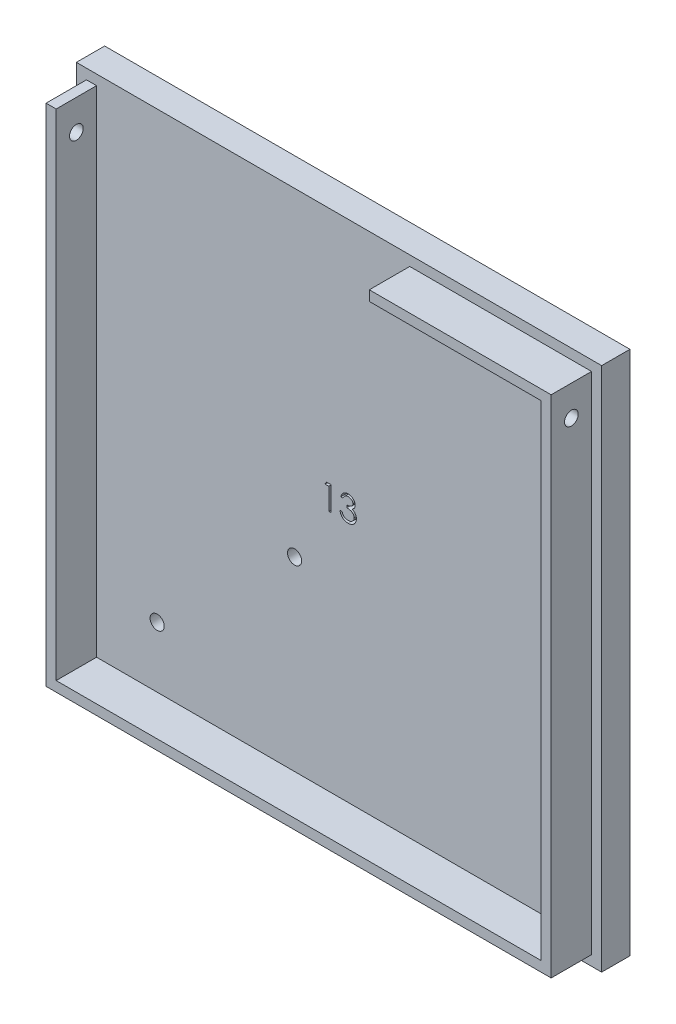
SolidWorks part; units mm, degrees
ref_plane "Alzado" through (0, 0, 0) normal (0, 0, 1) x (1, 0, 0)
ref_plane "Planta" through (0, 0, 0) normal (0, 1, 0) x (1, 0, 0)
ref_plane "Vista lateral" through (0, 0, 0) normal (1, 0, 0) x (0, 0, -1)
sketch "Croquis1" plane through (0, 0, 0) normal (0, 0, 1) x (1, 0, 0)
  line L1 (-65, -65) -> (65, -65)
  line L2 (-65, -65) -> (-65, 65)
  line L3 (-65, 65) -> (65, 65)
  line L4 (65, -65) -> (65, 65)
  circle A0 centre (-11, -14) radius 1.75
  circle A1 centre (-45, -45) radius 1.75
  circle A2 centre (55, 45) radius 2.25
  circle A3 centre (55, -45) radius 2.25
  point P0 (0, 0)
  dimension "D3" = 3.5
  dimension "D6" = 3.5
  dimension "D7" = 34
  dimension "D8" = 20
  dimension "D9" = 4.5
  dimension "D10" = 4.5
  dimension "D11" = 10
  dimension "D12" = 10
  dimension "D13" = 20
  dimension "D4" = 20
  dimension "D5" = 31
  dimension "D14" = 20
  dimension "D1" = 130
  dimension "D2" = 130
extrude "Saliente-Extruir1" add sketch "Croquis1" along normal blind 7
sketch "Croquis2" plane through (0, 0, 7) normal (0, 0, 1) x (1, 0, 0)
  line L0 (-65, 0) -> (65, 0) construction
  line L1 (-65, 65) -> (-65, -65) construction
  line L2 (65, -65) -> (65, 65) construction
  text T0 "13" font "Century Gothic" height 6
extrude "Cortar-Extruir1" cut sketch "Croquis2" against normal blind 2
sketch "Croquis4" plane through (0, 0, 7) normal (0, 0, 1) x (1, 0, 0)
  line L1 (-62.5, -62.5) -> (62.5, -62.5)
  line L2 (-62.5, -62.5) -> (-62.5, 62.5)
  line L3 (-62.5, 62.5) -> (62.5, 62.5)
  line L4 (62.5, -62.5) -> (62.5, 62.5)
  line L5 (-62.5, -62.5) -> (62.5, 62.5) construction
  line L6 (-62.5, 62.5) -> (62.5, -62.5) construction
  line L7 (60, -60) -> (-60, -60)
  line L8 (60, -60) -> (60, 60)
  line L9 (60, 60) -> (-60, 60)
  line L10 (-60, -60) -> (-60, 60)
  line L11 (60, -60) -> (-60, 60) construction
  line L12 (60, 60) -> (-60, -60) construction
  point P0 (0, 0)
  point P6 (0, 0)
  dimension "D1" = 120
  dimension "D2" = 120
  dimension "D3" = 125
extrude "Saliente-Extruir2" add sketch "Croquis4" along normal blind 10
sketch "Croquis6" plane through (62.5, 0, 0) normal (1, 0, 0) x (0, 0, -1)
  line L0 (-17, 62.5) -> (-7, 62.5) construction
  line L3 (-17, -62.5) -> (-17, 62.5) construction
  circle A0 centre (-12, 55) radius 1.7
  point P4 (-12, 62.5)
  dimension "D1" = 3.4
  dimension "D3" = 5
  dimension "D2" = 7.5
extrude "Cortar-Extruir2" cut sketch "Croquis6" against normal through all
sketch "Croquis7" plane through (0, 62.5, 0) normal (0, 1, 0) x (1, 0, 0)
  line L0 (62.5, -17) -> (-62.5, -17) construction
  line L1 (-60, -17) -> (17.5, -17)
  line L2 (-60, -17) -> (-60, -7)
  line L3 (-60, -7) -> (17.5, -7)
  line L4 (17.5, -17) -> (17.5, -7)
  line L5 (62.5, -7) -> (-62.5, -7) construction
  line L7 (-60, -17) -> (-60, -7) construction
  line L9 (60, -17) -> (60, -7) construction
  point P10 (-60, -12)
  dimension "D1" = 0
  dimension "D2" = 42.5
extrude "Cortar-Extruir3" cut sketch "Croquis7" against normal up to next
